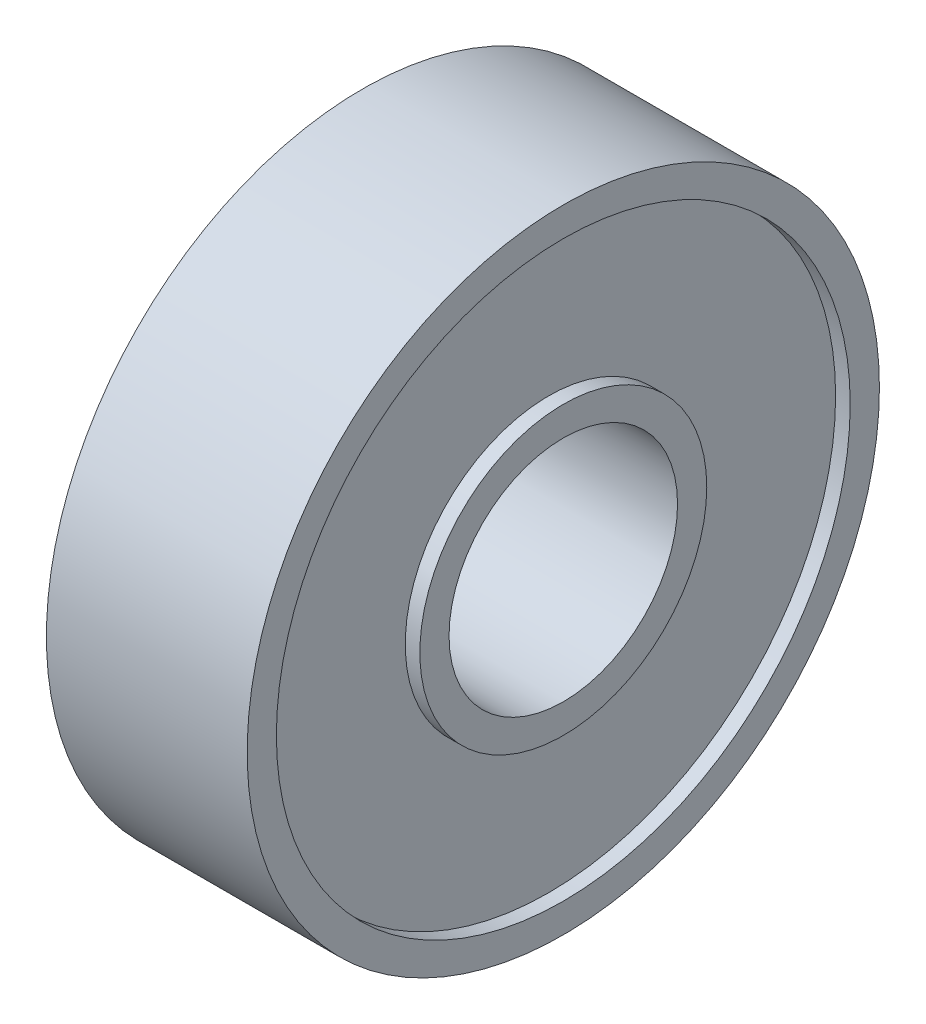
SolidWorks part; units mm, degrees
material "AISI 316 Stainless Steel Sheet (SS)"
ref_plane "Front Plane" through (0, 0, 0) normal (0, 0, 1) x (1, 0, 0)
ref_plane "Top Plane" through (0, 0, 0) normal (0, 1, 0) x (1, 0, 0)
ref_plane "Right Plane" through (0, 0, 0) normal (1, 0, 0) x (0, 0, -1)
sketch "Sketch1" plane through (0, 0, 0) normal (1, 0, 0) x (0, 0, -1)
  circle A0 centre (0, 0) radius 10.9982
  circle A1 centre (0, 0) radius 3.9751
  dimension "D1" = 21.9964
  dimension "D2" = 7.9502
extrude "Extrude1" add sketch "Sketch1" along normal blind 3.4925
sketch "Sketch2" plane through (3.4925, 0, 0) normal (1, 0, 0) x (0, 0, -1)
  circle A0 centre (0, 0) radius 4.9911
  circle A1 centre (0, 0) radius 9.9822
  circle A2 centre (0, 0) radius 10.9982 construction
  circle A3 centre (0, 0) radius 3.9751 construction
  dimension "D1" = 1.016
  dimension "D2" = 1.016
extrude "Extrude2" cut sketch "Sketch2" against normal blind 0.508
mirror "Mirror1" about plane through (0, 0, 0) normal (1, 0, 0) of "Extrude2", "Extrude1"
